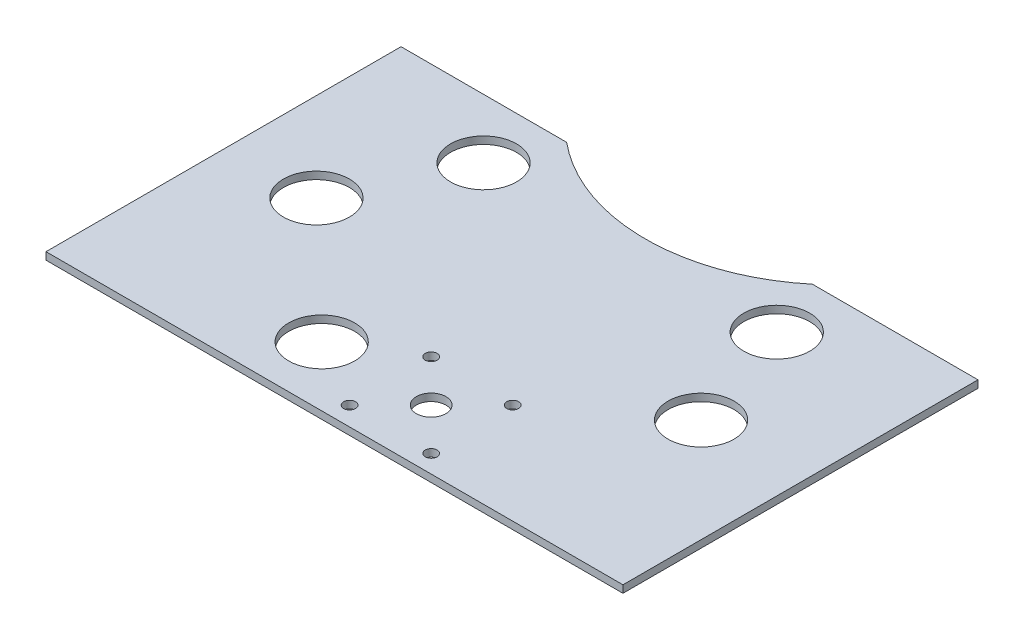
SolidWorks part; units mm, degrees
ref_plane "Front" through (0, 0, 0) normal (0, 0, 1) x (1, 0, 0)
ref_plane "Top" through (0, 0, 0) normal (0, 1, 0) x (1, 0, 0)
ref_plane "Right" through (0, 0, 0) normal (1, 0, 0) x (0, 0, -1)
sketch "Sketch1" plane through (0, 0, 0) normal (0, 1, 0) x (1, 0, 0)
  line L0 (-123.825, -55.88) -> (123.825, -55.88)
  line L1 (123.825, -55.88) -> (123.825, 96.52)
  line L2 (123.825, 96.52) -> (52.7471, 96.52)
  line L3 (-123.825, -55.88) -> (-123.825, 96.52)
  line L4 (-123.825, 96.52) -> (-52.7471, 96.52)
  arc A0 (-52.7471, 96.52) -> (52.7471, 96.52) centre (0, 160.02) ccw
  point P8 (0, -55.88)
  dimension "D1" = 165.1
  dimension "D2" = 152.4
  dimension "D3" = 247.65
  dimension "D4" = 63.5
  dimension "D5" = 55.88
extrude "Boss-Extrude1" add sketch "Sketch1" along normal blind 3.175 contours A0 L2 L1 L0 L3 L4
hole_wizard "1 (0.5) Dowel Hole1" positions "Sketch2" profile "Sketch3" hole size "1" standard "ANSI Inch" end condition through all
sketch "Sketch2" plane through (0, 3.175, 0) normal (0, 1, 0) x (1, 0, 0)
  circle A0 centre (15.875, -30.2569) radius 6.35 construction
  point P0 (15.875, -30.2569)
sketch "Sketch3" plane through (15.875, 3.175, 30.2569) normal (1, 0, 0) x (0, 0, 1)
  line L0 (0, 0) -> (0, 3.175)
  line L1 (0, 3.175) -> (6.35, 3.175)
  line L2 (6.35, 3.175) -> (6.35, 0)
  line L5 (6.35, 0) -> (0, 0)
  line L11 (0, -6.35) -> (0, 107.95) construction
  dimension "Thru Hole Dia." = 12.7
  dimension "Thru Hole Depth" = 3.175
hole_wizard "#10 Clearance Hole1" positions "Sketch4" profile "Sketch6" hole size "#10" standard "ANSI Inch" end condition up to next
sketch "Sketch4" plane through (0, 3.175, 0) normal (0, 1, 0) x (1, 0, 0)
  circle A0 centre (-1.625, -47.7569) radius 2.5527 construction
  circle A1 centre (33.375, -12.7569) radius 2.5527 construction
  circle A2 centre (33.8355, -48.2175) radius 2.5527 construction
  circle A3 centre (-2.0855, -12.2964) radius 2.5527 construction
  point P16 (-1.625, -47.7569)
  point P18 (33.375, -12.7569)
  point P25 (-2.0855, -12.2964)
  point P27 (33.8355, -48.2175)
sketch "Sketch6" plane through (-1.625, 3.175, 47.7569) normal (1, 0, 0) x (0, 0, 1)
  line L0 (0, 0) -> (0, 3.175)
  line L1 (0, 3.175) -> (2.5527, 3.175)
  line L2 (2.5527, 3.175) -> (2.5527, 0)
  line L5 (2.5527, 0) -> (0, 0)
  line L11 (0, -6.35) -> (0, 107.95) construction
  dimension "Thru Hole Dia." = 5.1054
  dimension "Thru Hole Depth" = 3.175
fillet "Fillet1" [suppressed] radius 38.1
hole_wizard "1 (1.115) Dowel Hole3" positions "Sketch9" profile "Sketch10" hole size "1" standard "ANSI Inch" end condition through all
sketch "Sketch9" plane through (-3.175, -34.925, 0) normal (0, -1, 0) x (-1, 0, 0)
  line L0 (82.55, 22.098) -> (-82.55, 22.098) construction
  point P0 (82.55, 22.098)
  point P2 (-82.55, 22.098)
sketch "Sketch10" plane through (-85.725, -34.925, -22.098) normal (1, 0, 0) x (0, 0, -1)
  line L0 (0, 0) -> (0, 38.1)
  line L1 (0, 38.1) -> (14.1605, 38.1)
  line L2 (14.1605, 38.1) -> (14.1605, 0)
  line L3 (14.1605, 0) -> (0, 0)
  line L4 (0, -6.35) -> (0, 107.95) construction
  dimension "Thru Hole Dia." = 28.321
  dimension "Thru Hole Depth" = 38.1
sketch "Sketch11" plane through (0, 3.175, 0) normal (0, 1, 0) x (1, 0, 0)
  line L0 (-31.115, -30.2569) -> (22.225, -30.2569) construction
  line L1 (-123.825, -55.88) -> (123.825, -55.88) construction
  circle A0 centre (-31.115, -30.2569) radius 14.1605
  circle A1 centre (15.875, -30.2569) radius 6.35 construction
  dimension "D1" = 28.321
  dimension "D2" = 53.34
extrude "Cut-Extrude1" cut sketch "Sketch11" against normal through all
sketch "Sketch12" plane through (0, 3.175, 0) normal (0, 1, 0) x (1, 0, 0)
  circle A0 centre (-62.9335, 71.035) radius 14.1605
  dimension "D1" = 28.321
extrude "Cut-Extrude2" cut sketch "Sketch12" against normal through all
mirror "Mirror2" about plane through (0, 0, 0) normal (1, 0, 0) of "Cut-Extrude2"
